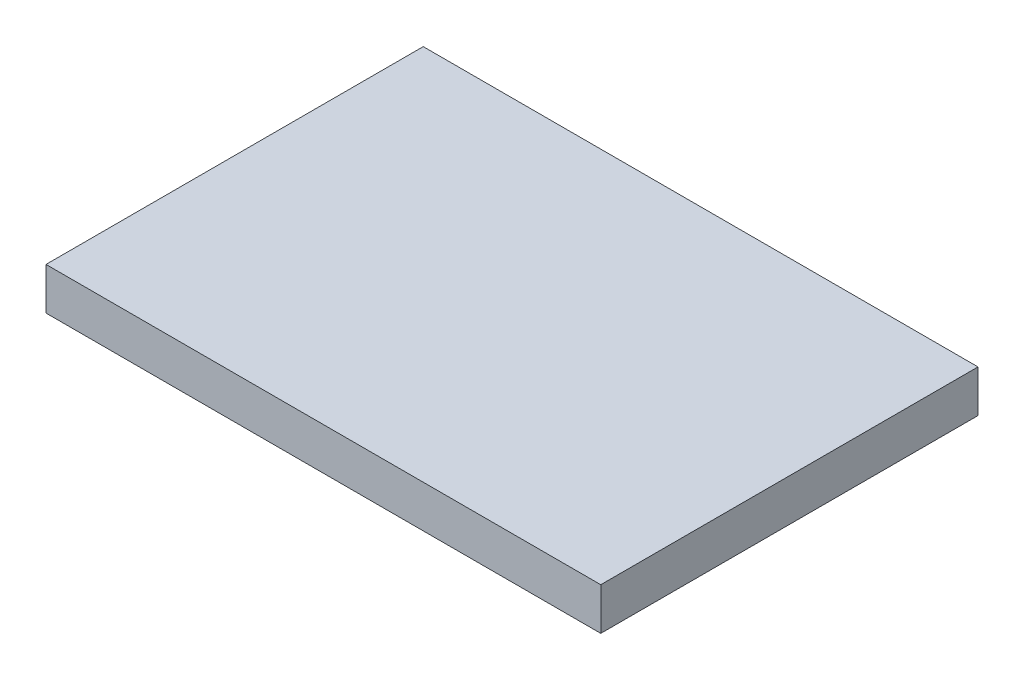
SolidWorks part; units mm, degrees
ref_plane "Front Plane" through (0, 0, 0) normal (0, 0, 1) x (1, 0, 0)
ref_plane "Top Plane" through (0, 0, 0) normal (0, 1, 0) x (1, 0, 0)
ref_plane "Right Plane" through (0, 0, 0) normal (1, 0, 0) x (0, 0, -1)
sketch "Sketch1" plane through (0, 0, 0) normal (0, 1, 0) x (1, 0, 0)
  line L1 (0, 0) -> (50, 0)
  line L2 (0, 0) -> (0, 34)
  line L3 (0, 34) -> (50, 34)
  line L4 (50, 0) -> (50, 34)
  dimension "D1" = 34
  dimension "D2" = 50
extrude "Boss-Extrude1" add sketch "Sketch1" along normal blind 3.8
